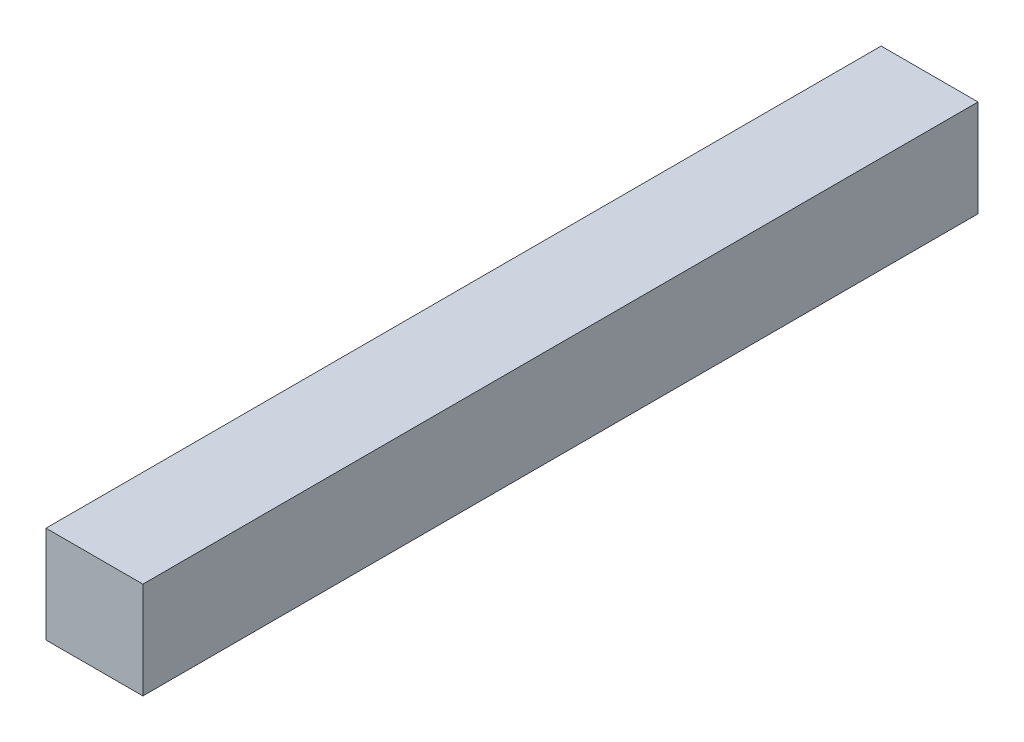
SolidWorks part; units mm, degrees
ref_plane "Front Plane" through (0, 0, 0) normal (0, 0, 1) x (1, 0, 0)
ref_plane "Top Plane" through (0, 0, 0) normal (0, 1, 0) x (1, 0, 0)
ref_plane "Right Plane" through (0, 0, 0) normal (1, 0, 0) x (0, 0, -1)
sketch "Sketch1" plane through (0, 0, 0) normal (0, 0, 1) x (1, 0, 0)
  line L1 (-3.625, 3.625) -> (3.625, 3.625)
  line L2 (-3.625, 3.625) -> (-3.625, -3.625)
  line L3 (-3.625, -3.625) -> (3.625, -3.625)
  line L4 (3.625, 3.625) -> (3.625, -3.625)
  line L5 (-3.625, 3.625) -> (3.625, -3.625) construction
  line L6 (-3.625, -3.625) -> (3.625, 3.625) construction
  point P0 (0, 0)
  dimension "D1" = 7.25
  dimension "D2" = 7.25
extrude "Boss-Extrude1" add sketch "Sketch1" along normal blind 62.5
equation "\"width_key\"=7.25"
equation "\"length_key\"=62.50"
equation "\"D2@Sketch1\"=\"width_key\""
equation "\"D1@Sketch1\"=\"width_key\""
equation "\"D1@Boss-Extrude1\"=\"length_key\""
